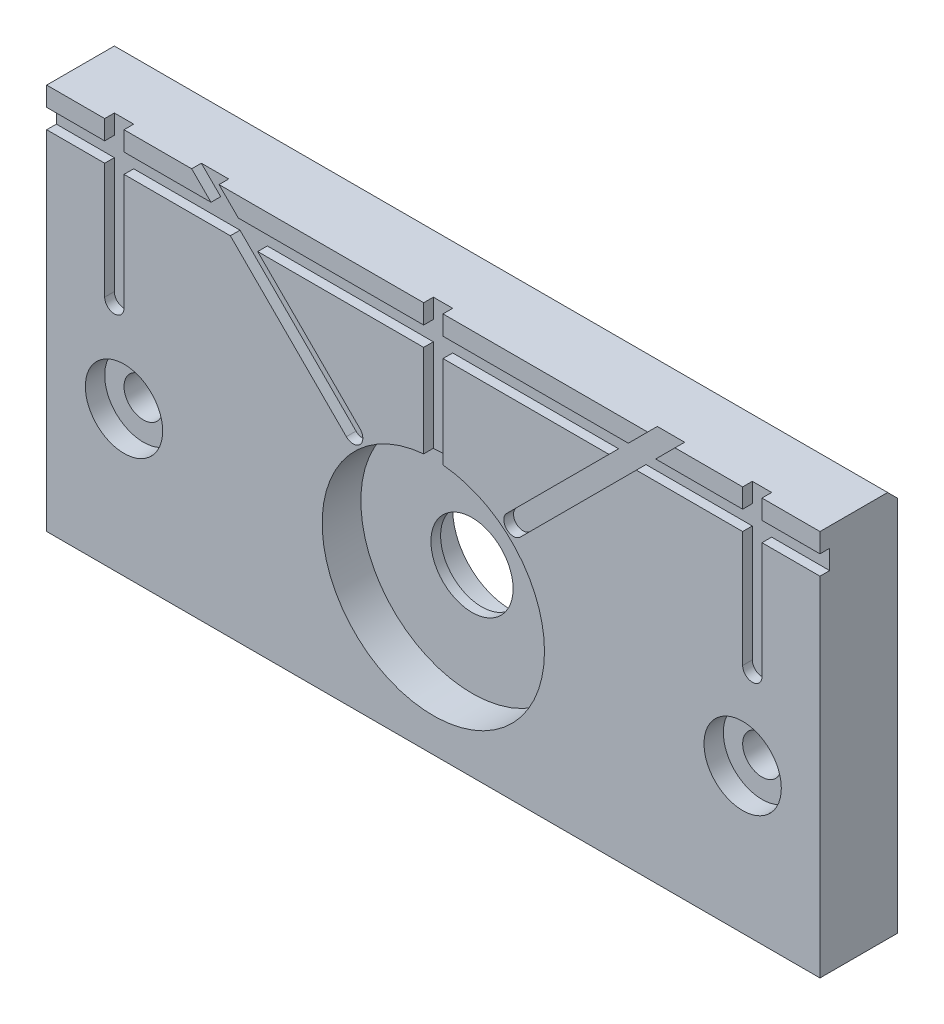
SolidWorks part; units mm, degrees
ref_plane "前视基准面" through (0, 0, 0) normal (0, 0, 1) x (1, 0, 0)
ref_plane "上视基准面" through (0, 0, 0) normal (0, 1, 0) x (1, 0, 0)
ref_plane "右视基准面" through (0, 0, 0) normal (1, 0, 0) x (0, 0, -1)
other "Configuration Table"
ref_plane "基准面1" through (0, 0, 8) normal (0, 0, 1) x (1, 0, 0)
sketch "草图1" plane through (0, 0, 8) normal (0, 0, 1) x (1, 0, 0)
  line L0 (80, -19.1667) -> (80, 40.8333)
  line L1 (80, 40.8333) -> (0, 40.8333)
  line L2 (0, 40.8333) -> (0, -19.1667)
  line L3 (0, -19.1667) -> (80, -19.1667)
  dimension "D1" = 80
  dimension "D2" = 60
extrude "凸台-拉伸1" add sketch "草图1" against normal blind 8
hole_wizard "M3.5 六角头机械螺钉的柱形沉头孔1" positions "草图13" profile "草图12" counterbore size "M3.5" standard "ANSI Metric" end condition through all
sketch "草图13" plane through (0, 0, 8) normal (0, 0, 1) x (1, 0, 0)
  line L1 (0, 15.8333) -> (80, 15.8333) construction
  line L2 (0, 40.8333) -> (0, -19.1667) construction
  line L3 (80, -19.1667) -> (80, 40.8333) construction
  line L4 (80, 40.8333) -> (0, 40.8333) construction
  point P0 (8, 15.8333)
  point P1 (72, 15.8333)
  point P13 (0, 0)
  point P14 (0, 0)
  dimension "D1" = 8
  dimension "D2" = 8
  dimension "D3" = 25
sketch "草图12" plane through (8, 15.8333, 8) normal (1, 0, 0) x (0, -1, 0)
  line L0 (0, 0) -> (0, 8)
  line L1 (0, 8) -> (2, 8)
  line L3 (2, 8) -> (2, 2)
  line L4 (2, 2) -> (4, 2)
  line L5 (4, 2) -> (4, 0)
  line L7 (4, 0) -> (0, 0)
  line L11 (0, -6.35) -> (0, 107.95) construction
  dimension "通孔孔直径" = 4
  dimension "通孔孔深度" = 8
  dimension "柱形沉头孔直径" = 8
  dimension "柱形沉头孔深度" = 2
sketch "草图14" plane through (0, 0, 8) normal (0, 0, 1) x (1, 0, 0)
  line L0 (40, 40.8333) -> (40, -19.1667) construction
  line L1 (80, 40.8333) -> (0, 40.8333) construction
  line L2 (0, -19.1667) -> (80, -19.1667) construction
  line L3 (0, 40.8333) -> (0, -19.1667) construction
  line L4 (0, 38.8333) -> (80, 38.8333)
  line L5 (0, 38.8333) -> (0, 36.8333)
  line L6 (0, 36.8333) -> (80, 36.8333)
  line L7 (40, 38.8333) -> (40, 36.8333)
  line L8 (80, -19.1667) -> (80, 40.8333) construction
  line L9 (15, 40.8333) -> (31, 24.8333)
  line L10 (6, 40.8333) -> (8, 40.8333)
  line L11 (6, 40.8333) -> (6, 24.8333)
  line L12 (6, 24.8333) -> (8, 24.8333)
  line L13 (8, 40.8333) -> (8, 24.8333)
  line L18 (39, 40.8333) -> (41, 40.8333)
  line L19 (39, 40.8333) -> (39, 24.8333)
  line L20 (39, 24.8333) -> (41, 24.8333)
  line L21 (40, 40.8333) -> (40, 24.8333)
  line L22 (31, 24.8333) -> (32.4142, 26.2475)
  line L23 (32.4142, 26.2475) -> (16.4142, 42.2475)
  line L24 (16.4142, 42.2475) -> (15, 40.8333)
  line L25 (0, 24.8333) -> (80, 24.8333) construction
  line L26 (74, 24.8333) -> (72, 24.8333)
  line L27 (72, 40.8333) -> (72, 24.8333)
  line L28 (74, 40.8333) -> (72, 40.8333)
  line L29 (74, 40.8333) -> (74, 24.8333)
  line L30 (47.5858, 26.2475) -> (63.5858, 42.2475)
  line L31 (49, 24.8333) -> (47.5858, 26.2475)
  line L32 (65, 40.8333) -> (49, 24.8333)
  line L33 (63.5858, 42.2475) -> (65, 40.8333)
  line L34 (41, 40.8333) -> (41, 24.8333)
  line L35 (80, 38.8333) -> (80, 36.8333)
  dimension "D1" = 2
  dimension "D2" = 2
  dimension "D3" = 6
  dimension "D4" = 2
  dimension "D5" = 16
  dimension "D6" = 2
  dimension "D7" = 1
  dimension "D8" = 7
  dimension "D9" = 45
extrude "切除-拉伸1" cut sketch "草图14" against normal blind 1 contours L4 L35 L6 L5 | L13 L12 L11 L10 | L9 L22 L23 L24 | L19 L20 L34 L18 | L30 L33 L32 L31 | L27 L26 L29 L28
sketch "草图15" plane through (0, 0, 8) normal (0, 0, 1) x (1, 0, 0)
  line L0 (40, 40.8333) -> (40, -19.1667) construction
  line L1 (39, 40.8333) -> (41, 40.8333) construction
  line L2 (0, -19.1667) -> (80, -19.1667) construction
  line L3 (39, 40.8333) -> (17.8284, 40.8333) construction
  circle A0 centre (40, 15.8333) radius 4.25
  point P8 (0, 0)
  dimension "D1" = 8.5
  dimension "D2" = 25
extrude "切除-拉伸2" cut sketch "草图15" against normal up to next
sketch "草图17" plane through (0, 0, 8) normal (0, 0, 1) x (1, 0, 0)
  circle A0 centre (40, 15.8333) radius 11.5
  dimension "D1" = 23
extrude "切除-拉伸4" cut sketch "草图17" against normal blind 4
sketch "草图18" plane through (0, 0, 0) normal (0, 0, -1) x (-1, 0, 0)
  circle A0 centre (-40, 15.8333) radius 6
  dimension "D1" = 12
extrude "切除-拉伸5" cut sketch "草图18" against normal blind 3
chamfer "倒角1" distance 1.5 angle 45 2 edges at (74, 15.8333, 0) (10, 15.8333, 0)
chamfer "倒角2" distance 1 angle 45 1 edges at (40, 40.8333, 0)
sketch "草图20" plane through (0, 0, 8) normal (0, 0, 1) x (1, 0, 0)
  line L0 (80, -19.1667) -> (80, 36.8333) construction
  line L1 (0, -19.1667) -> (80, -19.1667)
  line L2 (0, -19.1667) -> (0, -13.1667)
  line L3 (0, -13.1667) -> (80, -13.1667)
  line L4 (80, -19.1667) -> (80, -13.1667)
  dimension "D1" = 6
extrude "切除-拉伸6" cut sketch "草图20" against normal blind 1
sketch "草图21" plane through (0, 0, 7) normal (0, 0, 1) x (1, 0, 0)
  line L0 (80, -19.1667) -> (80, -13.1667) construction
  line L1 (0, -19.1667) -> (80, -19.1667)
  line L2 (0, -19.1667) -> (0, -15.1667)
  line L3 (0, -15.1667) -> (80, -15.1667)
  line L4 (80, -19.1667) -> (80, -15.1667)
  dimension "D1" = 4
extrude "切除-拉伸7" cut sketch "草图21" against normal blind 1
sketch "草图22" plane through (0, 0, 6) normal (0, 0, 1) x (1, 0, 0)
  line L1 (0, -19.1667) -> (80, -19.1667)
  line L2 (0, -19.1667) -> (0, -17.1667)
  line L3 (0, -17.1667) -> (80, -17.1667)
  line L4 (80, -19.1667) -> (80, -17.1667)
  dimension "D1" = 2
extrude "切除-拉伸8" cut sketch "草图22" against normal blind 1
sketch "草图23" plane through (0, 0, 8) normal (0, 0, 1) x (1, 0, 0)
  line L0 (6, 24.8333) -> (8, 24.8333) construction
  line L1 (31, 24.8333) -> (32.4142, 26.2475) construction
  line L3 (49, 24.8333) -> (47.5858, 26.2475) construction
  line L4 (74, 24.8333) -> (72, 24.8333) construction
  circle A0 centre (7, 24.8333) radius 1
  circle A1 centre (31.7071, 25.5404) radius 1
  circle A3 centre (48.2929, 25.5404) radius 1
  circle A4 centre (73, 24.8333) radius 1
extrude "切除-拉伸9" cut sketch "草图23" against normal up to surface (1 mm away) up to face at (40, 35.7375, 7)
sketch "草图24" plane through (0, 0, 8) normal (0, 0, 1) x (1, 0, 0)
  line L0 (0, 36.8333) -> (0, -13.1667) construction
  line L1 (0, 0.8333) -> (80, 0.8333)
  line L2 (0, 0.8333) -> (0, -19.1667)
  line L3 (0, -19.1667) -> (80, -19.1667)
  line L4 (80, 0.8333) -> (80, -19.1667)
  dimension "D1" = 20
extrude "切除-拉伸10" cut sketch "草图24" against normal up to next
